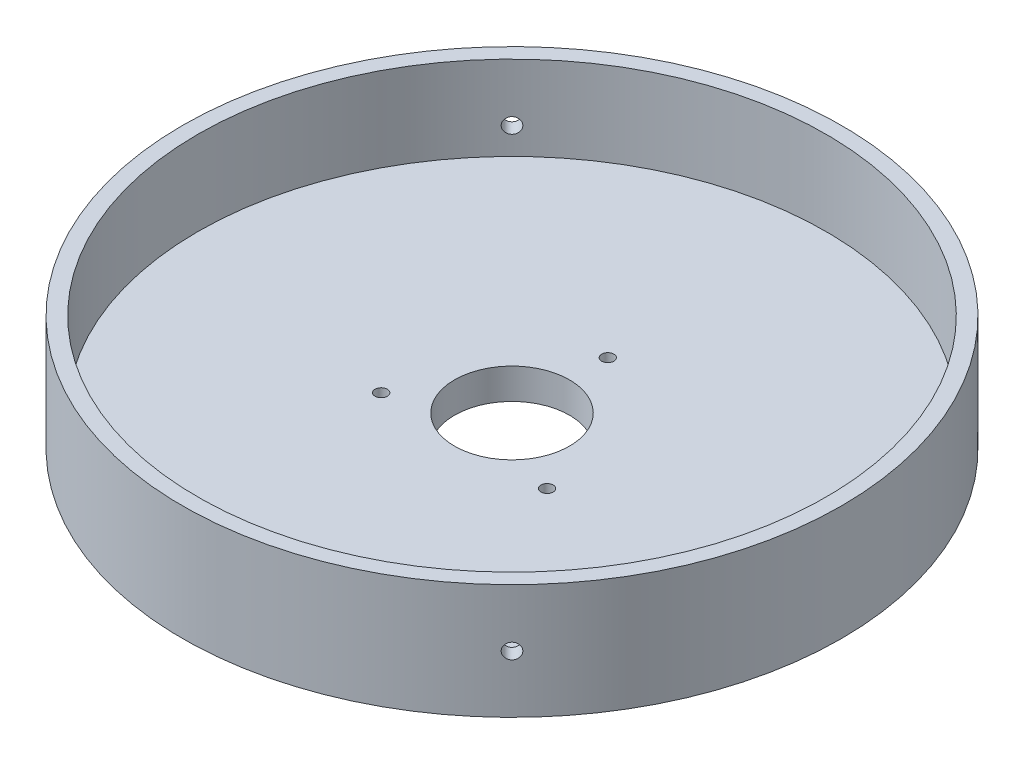
SolidWorks part; units mm, degrees
material "6061-T6 (SS)"
ref_plane "Front Plane" through (0, 0, 0) normal (0, 0, 1) x (1, 0, 0)
ref_plane "Top Plane" through (0, 0, 0) normal (0, 1, 0) x (1, 0, 0)
ref_plane "Right Plane" through (0, 0, 0) normal (1, 0, 0) x (0, 0, -1)
sketch "Sketch1" plane through (0, 0, 0) normal (0, 0, 1) x (1, 0, 0)
  line L0 (7.5, 0) -> (7.5, 4)
  line L1 (0, 0) -> (43, 0)
  line L2 (43, 0) -> (43, 15)
  line L3 (43, 15) -> (41, 15)
  line L4 (41, 15) -> (41, 4)
  line L5 (41, 4) -> (0, 4)
  line L6 (0, 4) -> (0, 0)
  dimension "D1" = 41
  dimension "D2" = 2
  dimension "D3" = 15
  dimension "D4" = 7.5
  dimension "D5" = 4
revolve "Revolve1" add sketch "Sketch1" angle 360 about L6
sketch "Sketch2" plane through (0, 4, 0) normal (0, 1, 0) x (1, 0, 0)
  line L0 (0, 0) -> (0, 12.5) construction
  circle A0 centre (0, 12.5) radius 0.8
  circle A1 centre (10.8253, -6.25) radius 0.8
  circle A2 centre (-10.8253, -6.25) radius 0.8
  dimension "D1" = 1.6
  dimension "D2" = 12.5
  dimension "D3" = 3
extrude "Cut-Extrude1" cut sketch "Sketch2" against normal through all
ref_plane "Plane1" through (0, 0, 0) normal (-0.7071, 0, 0.7071) x (0, -1, 0)
sketch "Sketch3" plane through (0, 0, 0) normal (-0.7071, 0, 0.7071) x (0.7071, 0, 0.7071)
  line L0 (0, 0) -> (0, 7.5) construction
  circle A0 centre (0, 7.5) radius 1
  dimension "D1" = 2
  dimension "D2" = 7.5
extrude "Cut-Extrude2" cut sketch "Sketch3" against normal through all
pattern_circular "CirPattern1" count 4 over 360 about axis through (0, 4, 0) along (0, 1, 0) of "Cut-Extrude2"
